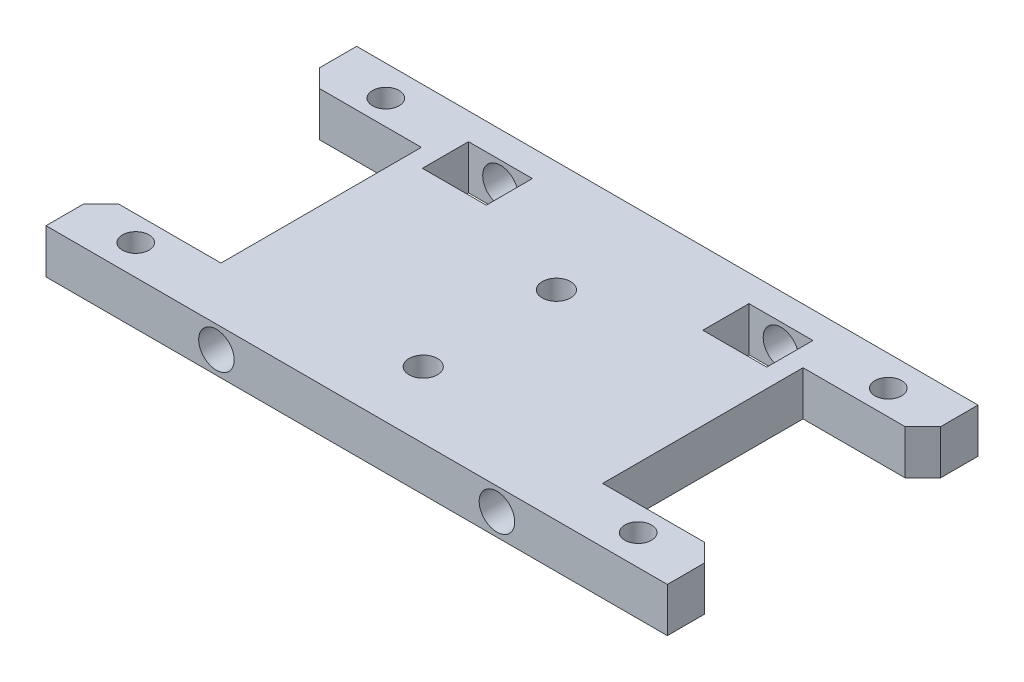
SolidWorks part; units mm, degrees
ref_plane "前视基准面" through (0, 0, 0) normal (0, 0, 1) x (1, 0, 0)
ref_plane "上视基准面" through (0, 0, 0) normal (0, 1, 0) x (1, 0, 0)
ref_plane "右视基准面" through (0, 0, 0) normal (1, 0, 0) x (0, 0, -1)
sketch "草图1" plane through (0, 0, 0) normal (0, 1, 0) x (1, 0, 0)
  line L0 (0, -1000.0249) -> (0, 48999.9751) construction
  line L9 (-35, 17.5) -> (35, 17.5)
  line L10 (-35, 17.5) -> (-35, -17.5)
  line L11 (-35, -17.5) -> (35, -17.5)
  line L12 (35, 17.5) -> (35, -17.5)
  line L13 (-35, 17.5) -> (35, -17.5) construction
  line L14 (-35, -17.5) -> (35, 17.5) construction
  line L18 (-21.5, 11.2886) -> (-21.5, -11.2886)
  line L24 (-35, -11.2886) -> (-35, 11.2886)
  line L32 (-21.5, 11.2886) -> (-35, 11.2886)
  line L33 (-21.5, -11.2886) -> (-35, -11.2886)
  line L34 (0, 0) -> (-50000, 0) construction
  line L37 (21.5, 11.2886) -> (21.5, -11.2886)
  line L38 (21.5, 11.2886) -> (35, 11.2886)
  line L39 (35, -11.2886) -> (35, 11.2886)
  line L40 (21.5, -11.2886) -> (35, -11.2886)
  circle A0 centre (-28.3037, 14.0886) radius 1.5
  circle A1 centre (-28.3037, -14.0886) radius 1.5
  circle A2 centre (28.3037, -14.0886) radius 1.5
  circle A3 centre (28.3037, 14.0886) radius 1.5
  circle A6 centre (0, -10) radius 1.6
  circle A7 centre (0, 5) radius 1.6
  point P0 (0, 0)
  point P8 (-21.5, 0)
  point P29 (0, -10)
  dimension "D3" = 2.8
  dimension "D5" = 3
  dimension "D6" = 3.4114
  dimension "D7" = 6.6963
  dimension "D10" = 3.2
  dimension "D11" = 3.2
  dimension "D12" = 15
  dimension "D1" = 35
  dimension "D2" = 70
  dimension "D8" = 13.5
  dimension "D13" = 10
extrude "凸台-拉伸1" add sketch "草图1" along normal blind 5
chamfer "倒角1" distance 2 angle 45 4 edges at (-35, 2.5, 11.2886) (-35, 2.5, -11.2886) (35, 2.5, 11.2886) (35, 2.5, -11.2886)
sketch "草图2" plane through (0, 0, 17.5) normal (0, 0, 1) x (1, 0, 0)
  line L0 (0, 0) -> (0, 50000) construction
  line L1 (-35, 5) -> (-35, 0) construction
  circle A0 centre (-15.8, 2.5) radius 2
  circle A1 centre (15.8, 2.5) radius 2
  point P9 (-35, 2.5)
  dimension "D1" = 15.8
  dimension "D2" = 4
extrude "切除-拉伸1" cut sketch "草图2" against normal through all contours A1 | A0
sketch "草图3" plane through (0, 5, 0) normal (0, 1, 0) x (1, 0, 0)
  line L1 (-19.4, 14.5) -> (-12.2, 14.5)
  line L2 (-19.4, 14.5) -> (-19.4, 9.3)
  line L3 (-19.4, 9.3) -> (-12.2, 9.3)
  line L4 (-12.2, 14.5) -> (-12.2, 9.3)
  line L5 (-19.4, 14.5) -> (-12.2, 9.3) construction
  line L6 (-19.4, 9.3) -> (-12.2, 14.5) construction
  line L8 (0, -55) -> (0, 55) construction
  line L9 (19.4, 9.3) -> (12.2, 14.5) construction
  line L10 (19.4, 14.5) -> (12.2, 9.3) construction
  line L11 (12.2, 14.5) -> (12.2, 9.3)
  line L12 (19.4, 9.3) -> (12.2, 9.3)
  line L13 (19.4, 14.5) -> (19.4, 9.3)
  line L14 (19.4, 14.5) -> (12.2, 14.5)
  line L15 (-35, 17.5) -> (35, 17.5) construction
  point P0 (-15.8, 11.9)
  point P15 (15.8, 11.9)
  dimension "D1" = 7.2
  dimension "D2" = 5.2
  dimension "D3" = 3
extrude "切除-拉伸2" cut sketch "草图3" against normal through all
